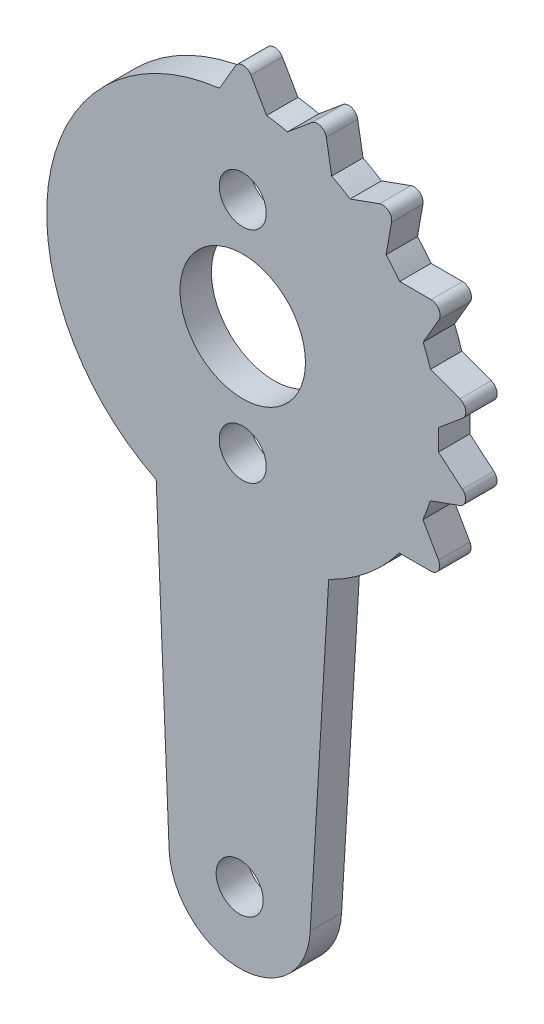
SolidWorks part; units mm, degrees
ref_plane "Front Plane" through (0, 0, 0) normal (0, 0, 1) x (1, 0, 0)
ref_plane "Top Plane" through (0, 0, 0) normal (0, 1, 0) x (1, 0, 0)
ref_plane "Right Plane" through (0, 0, 0) normal (1, 0, 0) x (0, 0, -1)
sketch "Sketch1" plane through (0, 0, 0) normal (0, 0, 1) x (1, 0, 0)
  line L0 (-5.3228, 19.8328) -> (-4.5, -0.185)
  line L1 (5.6772, 19.8147) -> (4.5, -0.1853)
  line L2 (4.5859, 44.5001) -> (3.0506, 43.2183)
  line L3 (0.7204, 45.1904) -> (1.7162, 43.4559)
  line L4 (-0.2796, 45.1904) -> (-1.2838, 43.4608)
  line L5 (5.5255, 44.158) -> (5.868, 42.1876)
  line L6 (8.9217, 42.1873) -> (7.0407, 41.5079)
  line L7 (9.6878, 41.5445) -> (9.3356, 39.5758)
  line L8 (12.2051, 38.5311) -> (10.2051, 38.536)
  line L9 (12.7051, 37.665) -> (11.7008, 35.9355)
  line L10 (14.04, 33.9723) -> (12.1623, 34.661)
  line L11 (14.2136, 32.9875) -> (12.6784, 31.7058)
  line L12 (14.205, 29.061) -> (12.6761, 30.3504)
  line L13 (14.0314, 28.0762) -> (12.1503, 27.3968)
  line L14 (12.6803, 24.3894) -> (11.6846, 26.1239)
  line L15 (12.1803, 23.5233) -> (10.1803, 23.5283)
  line L16 (0.1956, 31.0487) -> (0.1956, 38.0487) construction
  line L17 (0.1956, 31.0487) -> (0.1956, 24.0487) construction
  arc A0 (-5.3228, 19.8328) -> (-1.2838, 43.4608) centre (0.1956, 31.0487) cw
  arc A1 (-4.5, -0.185) -> (4.5, -0.1853) centre (0, 0) ccw
  circle A2 centre (0.1956, 31.0487) radius 4
  circle A3 centre (0.1956, 38.0487) radius 1.5
  circle A4 centre (0.1956, 24.0487) radius 1.5
  circle A5 centre (0, 0) radius 1.5
  arc A6 (-0.2796, 45.1904) -> (0.7204, 45.1904) centre (0.2204, 44.9001) cw
  arc A7 (1.7162, 43.4559) -> (3.0506, 43.2183) centre (0.1956, 31.0487) cw
  arc A8 (4.5859, 44.5001) -> (5.5255, 44.158) centre (4.9564, 44.0562) cw
  arc A9 (8.9217, 42.1873) -> (9.6878, 41.5445) centre (9.1181, 41.6435) cw
  arc A10 (12.2051, 38.5311) -> (12.7051, 37.665) centre (12.2037, 37.9529) cw
  arc A11 (14.04, 33.9723) -> (14.2136, 32.9875) centre (13.8409, 33.4295) cw
  arc A12 (14.205, 29.061) -> (14.0314, 28.0762) centre (13.8323, 28.619) cw
  arc A13 (12.6803, 24.3894) -> (12.1803, 23.5233) centre (12.1789, 24.1015) cw
  arc A14 (9.3356, 39.5758) -> (10.2051, 38.536) centre (0.1956, 31.0487) cw
  arc A15 (5.868, 42.1876) -> (7.0407, 41.5079) centre (0.1956, 31.0487) cw
  arc A16 (11.7008, 35.9355) -> (12.1623, 34.661) centre (0.1956, 31.0487) cw
  arc A17 (12.6784, 31.7058) -> (12.6761, 30.3504) centre (0.1956, 31.0487) cw
  arc A18 (12.1503, 27.3968) -> (11.6846, 26.1239) centre (0.1956, 31.0487) cw
  arc A19 (10.1803, 23.5283) -> (5.6772, 19.8147) centre (0.1956, 31.0487) cw
  point P50 (0.1956, 31.0487)
  dimension "D2" = 8
  dimension "D3" = 12.5
  dimension "D6" = 9
  dimension "D8" = 4.5038
  dimension "D11" = 3
  dimension "D7" = 11
  dimension "D9" = 20
  dimension "D10" = 31.0487
  dimension "D12" = 44.9001
  dimension "D13" = 7
  dimension "D14" = 2
  dimension "D15" = 2
  dimension "D16" = 1
extrude "Boss-Extrude1" add sketch "Sketch1" along normal blind 2
